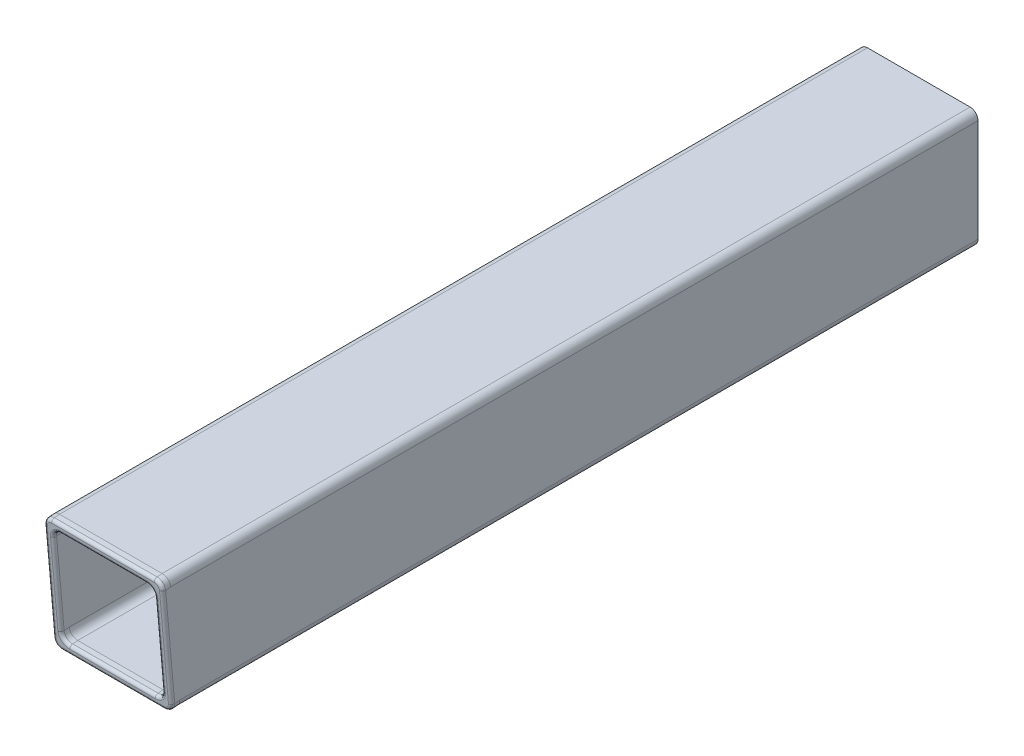
SolidWorks part; units mm, degrees
material "ASTM A500 Grade B Steel"
ref_plane "Front Plane" through (0, 0, 0) normal (0, 0, 1) x (1, 0, 0)
ref_plane "Top Plane" through (0, 0, 0) normal (0, 1, 0) x (1, 0, 0)
ref_plane "Right Plane" through (0, 0, 0) normal (1, 0, 0) x (0, 0, -1)
sketch "Sketch1" plane through (0, 0, 0) normal (0, 0, 1) x (1, 0, 0)
  line L0 (5.3086, -2.7686) -> (32.7914, -2.7686)
  line L1 (2.54, 0) -> (35.56, 0)
  line L2 (0, -2.54) -> (0, -35.56)
  line L3 (2.54, -38.1) -> (35.56, -38.1)
  line L4 (38.1, -2.54) -> (38.1, -35.56)
  line L5 (35.3314, -5.3086) -> (35.3314, -32.7914)
  line L6 (5.3086, -35.3314) -> (32.7914, -35.3314)
  line L7 (2.7686, -5.3086) -> (2.7686, -32.7914)
  line L8 (0, 0) -> (0, -38.1) construction
  line L9 (0, -38.1) -> (38.1, -38.1) construction
  line L10 (38.1, 0) -> (38.1, -38.1) construction
  line L11 (2.7686, -2.7686) -> (2.7686, -35.3314) construction
  line L12 (2.7686, -35.3314) -> (35.3314, -35.3314) construction
  line L13 (35.3314, -2.7686) -> (35.3314, -35.3314) construction
  line L14 (2.7686, -2.7686) -> (35.3314, -2.7686) construction
  line L15 (0, 0) -> (38.1, 0) construction
  arc A0 (0, -35.56) -> (2.54, -38.1) centre (2.54, -35.56) ccw
  arc A1 (38.1, -35.56) -> (35.56, -38.1) centre (35.56, -35.56) cw
  arc A2 (2.7686, -32.7914) -> (5.3086, -35.3314) centre (5.3086, -32.7914) ccw
  arc A3 (32.7914, -35.3314) -> (35.3314, -32.7914) centre (32.7914, -32.7914) ccw
  arc A4 (35.3314, -5.3086) -> (32.7914, -2.7686) centre (32.7914, -5.3086) ccw
  arc A5 (38.1, -2.54) -> (35.56, 0) centre (35.56, -2.54) ccw
  arc A6 (0, -2.54) -> (2.54, 0) centre (2.54, -2.54) cw
  arc A7 (5.3086, -2.7686) -> (2.7686, -5.3086) centre (5.3086, -5.3086) ccw
  point P12 (0, -38.1)
  dimension "D4" = 2.54
  dimension "D3" = 2.7686
extrude "Boss-Extrude1" add sketch "Sketch1" along normal blind 260
sketch "Sketch2" plane through (38.1, 0, 0) normal (1, 0, 0) x (0, 0, -1)
  line L0 (-260, 0) -> (-256.6667, -38.1)
  line L1 (-260, -38.1) -> (0, -38.1) construction
  line L5 (-260, 0) -> (-260, -38.1)
  line L6 (-256.6667, -38.1) -> (-260, -38.1)
  dimension "D1" = 5
extrude "Cut-Extrude1" cut sketch "Sketch2" against normal through all
sketch "Sketch3" plane through (0, -22.5743, 258.025) normal (0, -0.0872, 0.9962) x (1, 0, 0)
  line L0 (35.3314, 17.3316) -> (35.3314, -10.2562) construction
  line L1 (32.7914, -12.8059) -> (5.3086, -12.8059) construction
  line L2 (2.7686, -10.2562) -> (2.7686, 17.3316) construction
  line L3 (5.3086, 19.8813) -> (32.7914, 19.8813) construction
  line L4 (2.54, -15.585) -> (35.56, -15.585)
  line L5 (38.1, -13.0353) -> (38.1, 20.1108)
  line L6 (35.56, 22.6605) -> (2.54, 22.6605)
  line L7 (0, 20.1108) -> (0, -13.0353)
  line L8 (2.54, -15.585) -> (35.56, -15.585)
  line L9 (38.1, -13.0353) -> (38.1, 20.1108)
  line L10 (35.56, 22.6605) -> (2.54, 22.6605)
  line L11 (0, 20.1108) -> (0, -13.0353)
  line L12 (35.3314, 17.3316) -> (35.3314, -10.2562)
  line L13 (32.7914, -12.8059) -> (5.3086, -12.8059)
  line L14 (2.7686, -10.2562) -> (2.7686, 17.3316)
  line L15 (5.3086, 19.8813) -> (32.7914, 19.8813)
  ellipse E0 centre (32.7914, 17.3316) end of major axis (32.7914, 14.7819) minor radius 2.54 (35.3314, 17.3316) -> (32.7914, 19.8813) ccw construction
  ellipse E1 centre (32.7914, -10.2562) end of major axis (32.7914, -12.8059) minor radius 2.54 (32.7914, -12.8059) -> (35.3314, -10.2562) ccw construction
  ellipse E2 centre (5.3086, -10.2562) end of major axis (5.3086, -12.8059) minor radius 2.54 (2.7686, -10.2562) -> (5.3086, -12.8059) ccw construction
  ellipse E3 centre (5.3086, 17.3316) end of major axis (5.3086, 14.7819) minor radius 2.54 (5.3086, 19.8813) -> (2.7686, 17.3316) ccw construction
  ellipse E4 centre (35.56, -13.0353) end of major axis (35.56, -15.585) minor radius 2.54 (35.56, -15.585) -> (38.1, -13.0353) ccw
  ellipse E5 centre (35.56, 20.1108) end of major axis (35.56, 17.5611) minor radius 2.54 (38.1, 20.1108) -> (35.56, 22.6605) ccw
  ellipse E6 centre (2.54, 20.1108) end of major axis (2.54, 17.5611) minor radius 2.54 (2.54, 22.6605) -> (0, 20.1108) ccw
  ellipse E7 centre (2.54, -13.0353) end of major axis (2.54, -15.585) minor radius 2.54 (0, -13.0353) -> (2.54, -15.585) ccw
  ellipse E8 centre (35.56, -13.0353) end of major axis (35.56, -15.585) minor radius 2.54 (35.56, -15.585) -> (38.1, -13.0353) ccw
  ellipse E9 centre (35.56, 20.1108) end of major axis (35.56, 17.5611) minor radius 2.54 (38.1, 20.1108) -> (35.56, 22.6605) ccw
  ellipse E10 centre (2.54, 20.1108) end of major axis (2.54, 17.5611) minor radius 2.54 (2.54, 22.6605) -> (0, 20.1108) ccw
  ellipse E11 centre (2.54, -13.0353) end of major axis (2.54, -15.585) minor radius 2.54 (0, -13.0353) -> (2.54, -15.585) ccw
  ellipse E12 centre (32.7914, 17.3316) end of major axis (32.7914, 14.7819) minor radius 2.54 (35.3314, 17.3316) -> (32.7914, 19.8813) ccw
  ellipse E13 centre (32.7914, -10.2562) end of major axis (32.7914, -12.8059) minor radius 2.54 (32.7914, -12.8059) -> (35.3314, -10.2562) ccw
  ellipse E14 centre (5.3086, -10.2562) end of major axis (5.3086, -12.8059) minor radius 2.54 (2.7686, -10.2562) -> (5.3086, -12.8059) ccw
  ellipse E15 centre (5.3086, 17.3316) end of major axis (5.3086, 14.7819) minor radius 2.54 (5.3086, 19.8813) -> (2.7686, 17.3316) ccw
  dimension "D1" = 0
extrude "Boss-Extrude2" add sketch "Sketch3" along normal up to surface (2.6244 mm away)
fillet "Fillet1" radius 1 16 edges at (0.7439, -0.9727, 262.5493) (19.05, -0.2287, 262.6144) (37.3561, -0.9727, 262.5493) (38.1, -19.2787, 260.9477) (37.3561, -37.5848, 259.3462) (19.05, -38.3287, 259.2811) (0.7439, -37.5848, 259.3462) (0, -19.2787, 260.9477) (19.05, -2.9973, 262.3722) (3.5125, -3.7413, 262.3071) (2.7686, -19.2787, 260.9477) (3.5125, -34.8162, 259.5884) (19.05, -35.5601, 259.5233) (34.5875, -34.8162, 259.5884) (35.3314, -19.2787, 260.9477) (34.5875, -3.7413, 262.3071)
